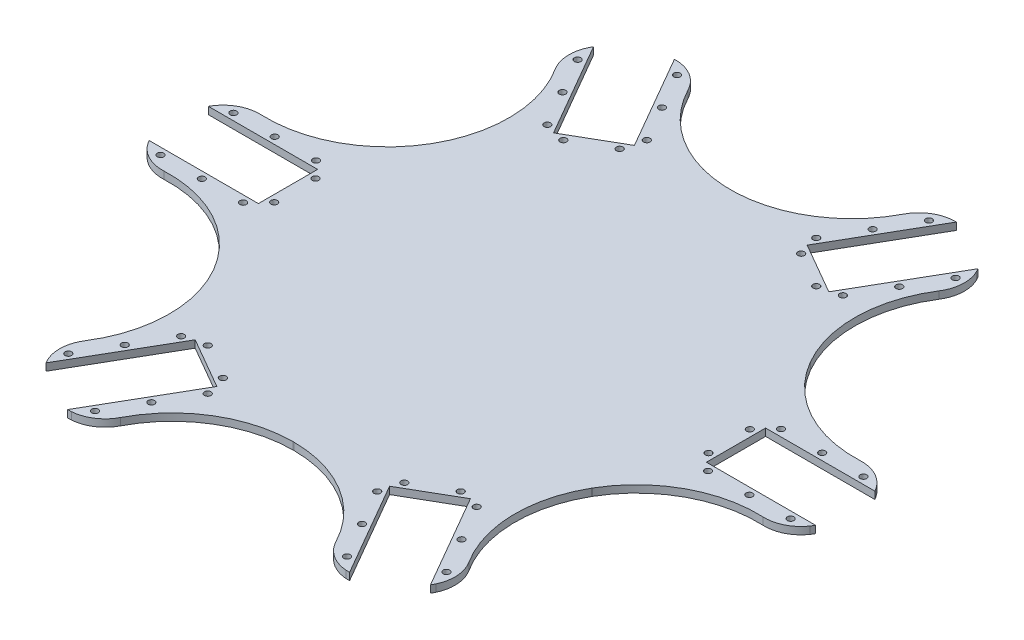
SolidWorks part; units mm, degrees
material "1060-H12"
ref_plane "Front Plane" through (0, 0, 0) normal (0, 0, 1) x (1, 0, 0)
ref_plane "Top Plane" through (0, 0, 0) normal (0, 1, 0) x (1, 0, 0)
ref_plane "Right Plane" through (0, 0, 0) normal (1, 0, 0) x (0, 0, -1)
sketch "Sketch2" plane through (0, 0, 0) normal (0, 1, 0) x (1, 0, 0)
  line L1 (0, 125) -> (-58.0814, 125)
  line L2 (-35.5814, 86.0289) -> (-56.7125, 73.8289)
  line L3 (-79.2125, 112.8) -> (-108.2532, 62.5)
  line L4 (-35.5814, 86.0289) -> (-58.0814, 125)
  line L7 (0, 0) -> (0, 125)
  line L8 (0, 0) -> (-108.2532, 62.5)
  line L12 (-79.2125, 112.8) -> (-56.7125, 73.8289)
  circle A0 centre (-37.3857, 81.754) radius 1.35
  circle A1 centre (-52.1082, 73.254) radius 1.35
  circle A2 centre (-60.8873, 75.4599) radius 1.35
  circle A3 centre (-34.9066, 90.4599) radius 1.35
  circle A4 centre (-51.9066, 119.9048) radius 1.35
  circle A5 centre (-43.4066, 105.1824) radius 1.35
  circle A6 centre (-69.3873, 90.1824) radius 1.35
  circle A7 centre (-77.8873, 104.9048) radius 1.35
  dimension "D3" = 3.5
  dimension "D5" = 2.8
  dimension "D9" = 34
  dimension "D13" = 2.8
  dimension "D14" = 2.8
  dimension "D2" = 3.5
  dimension "D4" = 17
  dimension "D12" = 17
  dimension "D15" = 17
  dimension "D16" = 34
extrude "Boss-Extrude1" add sketch "Sketch2" along normal blind 3
pattern_circular "CirPattern1" count 6 over 360 about axis through (0, 0, 0) along (0, 1, 0) of "Boss-Extrude1"
sketch "Sketch4" plane through (0, 3, 0) normal (0, 1, 0) x (1, 0, 0)
  line L0 (58.0814, 125) -> (-58.0814, 125) construction
  line L1 (137.2939, 12.2) -> (79.2125, 112.8) construction
  line L2 (79.2125, -112.8) -> (137.2939, -12.2) construction
  line L3 (-58.0814, -125) -> (58.0814, -125) construction
  line L4 (-137.2939, -12.2) -> (-79.2125, -112.8) construction
  line L5 (-79.2125, 112.8) -> (-137.2939, 12.2) construction
  line L6 (79.2125, -112.8) -> (137.2939, -12.2)
  line L8 (137.2939, 12.2) -> (79.2125, 112.8)
  line L10 (58.0814, 125) -> (-58.0814, 125)
  line L12 (-79.2125, 112.8) -> (-137.2939, 12.2)
  line L14 (-92.2939, -12.2) -> (-137.2939, -12.2) construction
  line L15 (-137.2939, -12.2) -> (-79.2125, -112.8)
  line L17 (-58.0814, -125) -> (58.0814, -125)
  arc A0 (-30.9451, 108.6476) -> (30.9451, 108.6476) centre (0, 125) ccw
  arc A1 (78.619, 81.123) -> (109.5641, 27.5246) centre (108.2532, 62.5) ccw
  arc A2 (109.5641, -27.5246) -> (78.619, -81.123) centre (108.2532, -62.5) ccw
  arc A4 (-78.619, -81.123) -> (-109.5641, -27.5246) centre (-108.2532, -62.5) ccw
  arc A5 (-109.5641, 27.5246) -> (-78.619, 81.123) centre (-108.2532, 62.5) ccw
  arc A6 (58.0814, 125) -> (30.9451, 108.6476) centre (58.0814, 94.3078) ccw
  arc A7 (-30.9451, 108.6476) -> (-58.0814, 125) centre (-58.0814, 94.3078) ccw
  arc A8 (-79.2125, 112.8) -> (-78.619, 81.123) centre (-52.6322, 97.4539) ccw
  arc A9 (-109.5641, 27.5246) -> (-137.2939, 12.2) centre (-110.7137, -3.1461) ccw
  arc A10 (109.5641, -27.5246) -> (137.2939, -12.2) centre (110.7137, 3.1461) ccw
  arc A11 (-58.0814, -125) -> (-30.9451, -108.6476) centre (-58.0814, -94.3078) ccw
  arc A12 (-78.619, -81.123) -> (-79.2125, -112.8) centre (-52.6322, -97.4539) ccw
  arc A13 (-137.2939, -12.2) -> (-109.5641, -27.5246) centre (-110.7137, 3.1461) ccw
  arc A14 (78.619, 81.123) -> (79.2125, 112.8) centre (52.6322, 97.4539) ccw
  arc A16 (79.2125, -112.8) -> (78.619, -81.123) centre (52.6322, -97.4539) ccw
  arc A19 (137.2939, 12.2) -> (109.5641, 27.5246) centre (110.7137, -3.1461) ccw
  arc A20 (30.9451, -108.6476) -> (-30.9451, -108.6476) centre (0, -125) ccw
  arc A21 (30.9451, -108.6476) -> (58.0814, -125) centre (58.0814, -94.3078) ccw
extrude "Cut-Extrude3" cut sketch "Sketch4" against normal blind 5
sketch "Sketch8" plane through (0, 3, 0) normal (0, 1, 0) x (1, 0, 0)
  line L0 (-57.6659, 125.0058) -> (58.0814, 125)
  line L1 (79.4252, 112.443) -> (137.2939, 12.2)
  line L2 (137.0912, -12.5628) -> (79.2125, -112.8001)
  line L3 (57.6659, -125.0058) -> (-58.0814, -125.0001)
  line L4 (-79.4252, -112.4431) -> (-137.2939, -12.2001)
  line L5 (-137.0912, 12.5627) -> (-79.2125, 112.8)
  arc A0 (-44.3583, 116.9274) -> (44.3583, 116.9275) centre (0, 140) ccw
  arc A1 (-30.9451, 108.6476) -> (30.9451, 108.6476) centre (0, 125) ccw construction
  arc A2 (-44.3583, 116.9274) -> (-57.6644, 125.0058) centre (-57.6659, 110.0056) ccw
  arc A3 (58.0814, 125) -> (44.3583, 116.9275) centre (57.6658, 110.0057) ccw
  arc A4 (79.083, 96.8791) -> (79.426, 112.4417) centre (66.4347, 104.9429) ccw
  arc A5 (79.083, 96.8791) -> (123.4414, 20.0483) centre (121.2436, 70) ccw
  arc A6 (137.2939, 12.2) -> (123.4414, 20.0483) centre (124.1007, 5.0628) ccw
  arc A7 (123.4413, -20.0484) -> (137.0904, -12.5641) centre (124.1006, -5.0627) ccw
  arc A8 (123.4413, -20.0484) -> (79.0831, -96.8792) centre (121.2436, -70.0001) ccw
  arc A9 (79.2125, -112.8001) -> (79.0831, -96.8792) centre (66.4349, -104.943) ccw
  arc A10 (44.3583, -116.9275) -> (57.6644, -125.0058) centre (57.6659, -110.0056) ccw
  arc A11 (44.3583, -116.9275) -> (-44.3583, -116.9276) centre (0, -140.0001) ccw
  arc A12 (-58.0814, -125.0001) -> (-44.3583, -116.9276) centre (-57.6658, -110.0058) ccw
  arc A13 (-79.083, -96.8792) -> (-79.426, -112.4418) centre (-66.4347, -104.943) ccw
  arc A14 (-79.083, -96.8792) -> (-123.4414, -20.0484) centre (-121.2436, -70.0001) ccw
  arc A15 (-137.2939, -12.2001) -> (-123.4414, -20.0484) centre (-124.1007, -5.0629) ccw
  arc A16 (-123.4413, 20.0483) -> (-137.0904, 12.564) centre (-124.1006, 5.0626) ccw
  arc A17 (-123.4413, 20.0483) -> (-79.0831, 96.8792) centre (-121.2436, 70) ccw
  arc A18 (-79.2125, 112.8) -> (-79.0831, 96.8792) centre (-66.4349, 104.9429) ccw
  point P56 (0, 0)
  dimension "D1" = 6
extrude "Cut-Extrude9" cut sketch "Sketch8" against normal blind 10 contours A18 L5 A16 A17 | A15 L4 A13 A14 | A12 L3 A10 A11 | A9 L2 A7 A8 | A6 L1 A4 A5 | A3 L0 A2 A0
